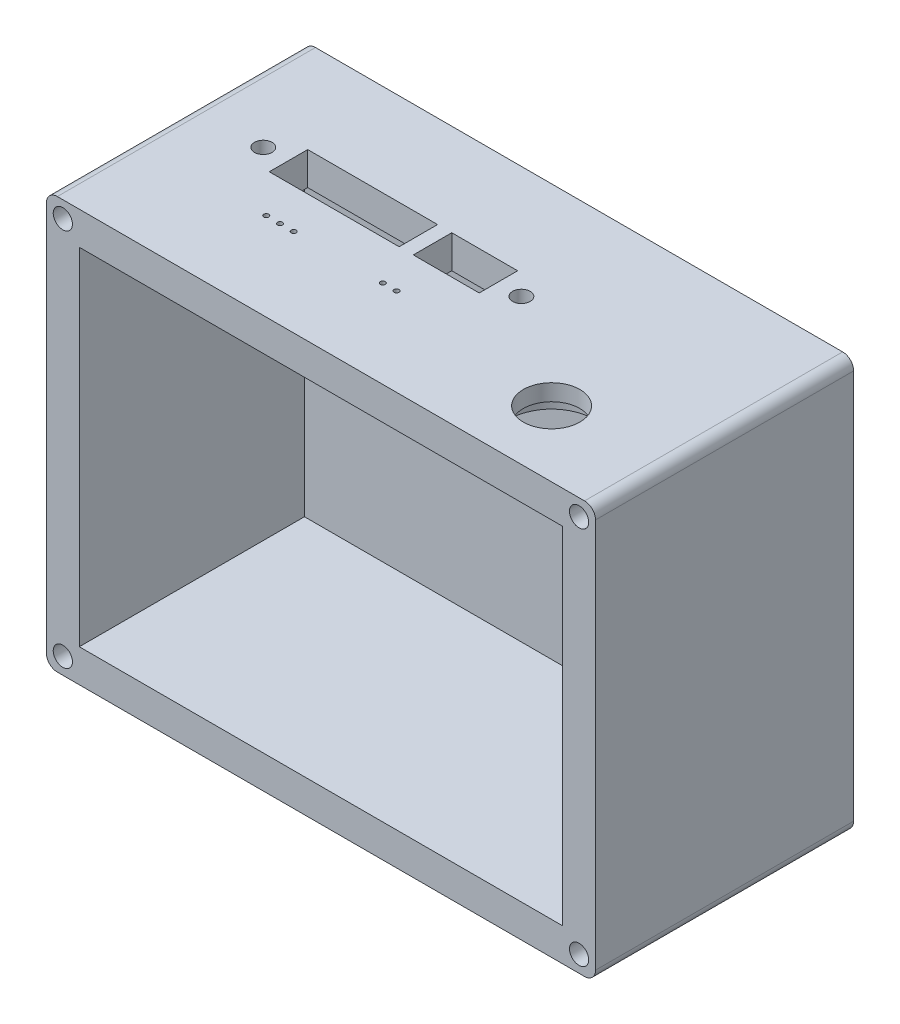
SolidWorks part; units mm, degrees
ref_plane "Plan de face" through (0, 0, 0) normal (0, 0, 1) x (1, 0, 0)
ref_plane "Plan de dessus" through (0, 0, 0) normal (0, 1, 0) x (1, 0, 0)
ref_plane "Plan de droite" through (0, 0, 0) normal (1, 0, 0) x (0, 0, -1)
sketch "Esquisse1" plane through (0, 0, 0) normal (0, 0, 1) x (1, 0, 0)
  line L1 (-50, 37.5) -> (50, 37.5)
  line L2 (-50, 37.5) -> (-50, -37.5)
  line L3 (-50, -37.5) -> (50, -37.5)
  line L4 (50, 37.5) -> (50, -37.5)
  line L5 (-50, 37.5) -> (50, -37.5) construction
  line L6 (-50, -37.5) -> (50, 37.5) construction
  point P0 (0, 0)
  dimension "D1" = 75
  dimension "D2" = 100
extrude "Boss.-Extru.1" add sketch "Esquisse1" along normal blind 47
shell "Coque1" thickness 6
sketch "Esquisse6" plane through (0, 0, 47) normal (0, 0, 1) x (1, 0, 0)
  line L0 (-50, 37.5) -> (-44, 31.5) construction
  line L1 (0, -25.85) -> (0, 25.85) construction
  line L2 (25.85, 0) -> (-25.85, 0) construction
  circle A0 centre (-47, 34.5) radius 1.75
  circle A2 centre (47, 34.5) radius 1.75
  circle A3 centre (47, -34.5) radius 1.75
  circle A4 centre (-47, -34.5) radius 1.75
  point P4 (-47, 34.5)
  dimension "0.5" = 3.5
extrude "Enlèv. mat.-Extru.1" cut sketch "Esquisse6" against normal blind 7.3
sketch "Esquisse7" plane through (0, 0, 0) normal (0, 0, -1) x (-1, 0, 0)
  line L0 (-50, 37.5) -> (50, 37.5) construction
  line L1 (-50, -37.5) -> (-50, 37.5) construction
  line L2 (0, 25.85) -> (0, -25.85) construction
  line L3 (25.85, 0) -> (-25.85, 0) construction
  circle A0 centre (-35, 22.5) radius 10
  circle A1 centre (35, 22.5) radius 10
  circle A2 centre (-35, -22.5) radius 10
  circle A3 centre (35, -22.5) radius 10
  dimension "D1" = 20
  dimension "D3" = 15
  dimension "D2" = 15
extrude "Enlèv. mat.-Extru.2" cut sketch "Esquisse7" against normal blind 0.5
sketch "Esquisse8" plane through (0, 37.5, 0) normal (0, 1, 0) x (1, 0, 0)
  line L0 (0, 0) -> (0, -47) construction
  line L1 (50, -47) -> (-50, -47) construction
  line L2 (-40, -20) -> (-40, -28.5)
  line L7 (-35, -15) -> (8, -15)
  line L8 (13, -20) -> (13, -28.5)
  line L9 (-35, -33.5) -> (8, -33.5)
  line L10 (-50, -47) -> (-50, 0) construction
  line L11 (50, 0) -> (-50, 0) construction
  line L13 (-32.61, -16.8) -> (-8.96, -16.8)
  line L14 (-32.61, -16.8) -> (-32.61, -23.8)
  line L15 (-32.61, -23.8) -> (-8.96, -23.8)
  line L16 (-8.96, -16.8) -> (-8.96, -23.8)
  line L17 (-32.61, -16.8) -> (-8.96, -23.8) construction
  line L18 (-32.61, -23.8) -> (-8.96, -16.8) construction
  line L19 (-6.38, -16.8) -> (5.62, -16.8)
  line L20 (-6.38, -16.8) -> (-6.38, -23.8)
  line L21 (-6.38, -23.8) -> (5.62, -23.8)
  line L22 (5.62, -16.8) -> (5.62, -23.8)
  line L23 (-6.38, -16.8) -> (5.62, -23.8) construction
  line L24 (-6.38, -23.8) -> (5.62, -16.8) construction
  arc A0 (-40, -20) -> (-35, -15) centre (-35, -20) cw
  arc A1 (8, -15) -> (13, -20) centre (8, -20) cw
  arc A2 (-40, -28.5) -> (-35, -33.5) centre (-35, -28.5) ccw
  arc A3 (13, -28.5) -> (8, -33.5) centre (8, -28.5) cw
  circle A4 centre (-37, -20.5) radius 1.6
  circle A5 centre (10, -20.5) radius 1.6
  circle A6 centre (-25.96, -31) radius 0.455
  circle A7 centre (-23.46, -31) radius 0.455
  circle A8 centre (-20.96, -31) radius 0.455
  circle A9 centre (-4.73, -31) radius 0.455
  circle A10 centre (-2.23, -31) radius 0.455
  point P26 (-20.785, -20.3)
  point P31 (-0.38, -20.3)
  point P46 (0, 0)
  dimension "D2" = 5
  dimension "D4" = 5
  dimension "D5" = 10
  dimension "D6" = 20
  dimension "D8" = 5.5
  dimension "D9" = 3.2
  dimension "D10" = 5.5
  dimension "D11" = 3
  dimension "D12" = 3.2
  dimension "D21" = 0.91
  dimension "D22" = 15.23
  dimension "D23" = 2.5
  dimension "D24" = 2.5
  dimension "D25" = 2.5
  dimension "D26" = 16.23
  dimension "D27" = 2.5
  dimension "D1" = 8.5
  dimension "D3" = 43
  dimension "D7" = 3
  dimension "D13" = 7.39
  dimension "D14" = 1.8
  dimension "D15" = 23.65
  dimension "D16" = 7
  dimension "D17" = 7.38
  dimension "D18" = 1.8
  dimension "D19" = 7
  dimension "D20" = 12
sketch "Esquisse9" plane through (0, 37.5, 0) normal (0, 1, 0) x (1, 0, 0)
  line L0 (5.62, -16.8) -> (5.62, -23.8) construction
  line L1 (-6.38, -16.8) -> (5.62, -16.8) construction
  line L2 (-6.38, -23.8) -> (5.62, -23.8) construction
  line L3 (-6.38, -16.8) -> (-6.38, -23.8) construction
  line L4 (-8.96, -16.8) -> (-8.96, -23.8) construction
  line L5 (-32.61, -16.8) -> (-8.96, -16.8) construction
  line L6 (-32.61, -23.8) -> (-8.96, -23.8) construction
  line L7 (-32.61, -16.8) -> (-32.61, -23.8) construction
  line L8 (5.62, -16.8) -> (5.62, -23.8)
  line L9 (-6.38, -16.8) -> (5.62, -16.8)
  line L10 (-6.38, -23.8) -> (5.62, -23.8)
  line L11 (-6.38, -16.8) -> (-6.38, -23.8)
  line L12 (-8.96, -16.8) -> (-8.96, -23.8)
  line L13 (-32.61, -16.8) -> (-8.96, -16.8)
  line L14 (-32.61, -23.8) -> (-8.96, -23.8)
  line L15 (-32.61, -16.8) -> (-32.61, -23.8)
  circle A0 centre (-4.73, -31) radius 0.455 construction
  circle A1 centre (-2.23, -31) radius 0.455 construction
  circle A2 centre (10, -20.5) radius 1.6 construction
  circle A3 centre (-20.96, -31) radius 0.455 construction
  circle A4 centre (-23.46, -31) radius 0.455 construction
  circle A5 centre (-25.96, -31) radius 0.455 construction
  circle A6 centre (-37, -20.5) radius 1.6 construction
  circle A7 centre (-4.73, -31) radius 0.455
  circle A8 centre (-2.23, -31) radius 0.455
  circle A9 centre (10, -20.5) radius 1.6
  circle A10 centre (-20.96, -31) radius 0.455
  circle A11 centre (-23.46, -31) radius 0.455
  circle A12 centre (-25.96, -31) radius 0.455
  circle A13 centre (-37, -20.5) radius 1.6
extrude "Enlèv. mat.-Extru.3" cut sketch "Esquisse9" against normal up to surface (6 mm away) up to face at (0, 31.5, 26.5)
sketch "Esquisse10" plane through (0, 37.5, 0) normal (0, 1, 0) x (1, 0, 0)
  line L0 (50, 0) -> (-50, 0) construction
  line L1 (50, -47) -> (50, 0) construction
  circle A0 centre (30, -35) radius 5.15
  dimension "D1" = 10.3
  dimension "D2" = 35
  dimension "D3" = 20
extrude "Enlèv. mat.-Extru.4" cut sketch "Esquisse10" against normal up to surface (6 mm away) up to face at (-20.785, 31.5, 20.3)
sketch "Esquisse11" plane through (0, 31.5, 0) normal (0, -1, 0) x (1, 0, 0)
  circle A0 centre (30, 35) radius 7.75
  dimension "D1" = 15.5
extrude "Enlèv. mat.-Extru.5" cut sketch "Esquisse11" against normal blind 3
fillet "Congé1" radius 2 4 edges at (-50, -37.5, 23.5) (-50, 37.5, 23.5) (50, 37.5, 23.5) (50, -37.5, 23.5)
